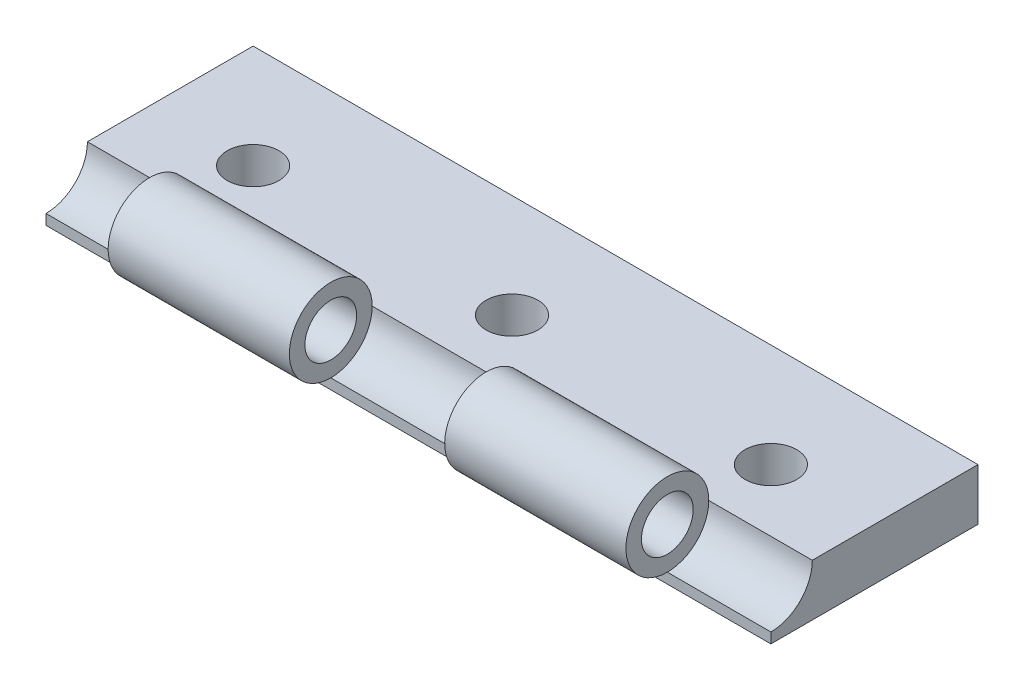
SolidWorks part; units mm, degrees
ref_plane "Front Plane" through (0, 0, 0) normal (0, 0, 1) x (1, 0, 0)
ref_plane "Top Plane" through (0, 0, 0) normal (0, 1, 0) x (1, 0, 0)
ref_plane "Right Plane" through (0, 0, 0) normal (1, 0, 0) x (0, 0, -1)
sketch "Sketch2" plane through (0, 0, 0) normal (0, 1, 0) x (1, 0, 0)
  line L1 (-44.45, 25.4) -> (44.45, 25.4)
  line L2 (-44.45, 25.4) -> (-44.45, 0)
  line L3 (-44.45, 0) -> (44.45, 0)
  line L4 (44.45, 25.4) -> (44.45, 0)
  line L5 (-44.45, 25.4) -> (44.45, 0) construction
  line L6 (-44.45, 0) -> (44.45, 25.4) construction
  circle A0 centre (-31.75, 12.7) radius 3.175
  circle A1 centre (0, 12.7) radius 3.175
  circle A2 centre (31.75, 12.7) radius 3.175
  point P0 (0, 12.7)
  point P12 (0, 0)
  point P15 (-24.5664, 19.719)
  dimension "D3" = 6.35
  dimension "D1" = 25.4
  dimension "D2" = 88.9
  dimension "D4" = 63.5
  dimension "D5" = 31.75
extrude "Boss-Extrude1" add sketch "Sketch2" along normal blind 6.35
sketch "Sketch3" plane through (-44.45, 0, 0) normal (-1, 0, 0) x (0, 0, 1)
  circle A0 centre (0, 6.35) radius 5.08
  dimension "D1" = 10.16
extrude "Cut-Extrude1" cut sketch "Sketch3" against normal through all
ref_plane "Plane1" through (9.525, 0, 0) normal (1, 0, 0) x (0, 0, -1)
sketch "Sketch4" plane through (9.525, 0, 0) normal (1, 0, 0) x (0, 0, -1)
  circle A0 centre (0, 6.35) radius 3.175
  arc A2 (0, 1.27) -> (5.08, 6.35) centre (0, 6.35) ccw construction
  circle A3 centre (0, 6.35) radius 5.08
  dimension "D1" = 6.35
extrude "Boss-Extrude2" add sketch "Sketch4" along normal blind 22.225
mirror "Mirror1" about plane through (0, 0, 0) normal (1, 0, 0) of "Boss-Extrude2"
equation "\"D5@Sketch2\"=\"D4@Sketch2\"/2"
